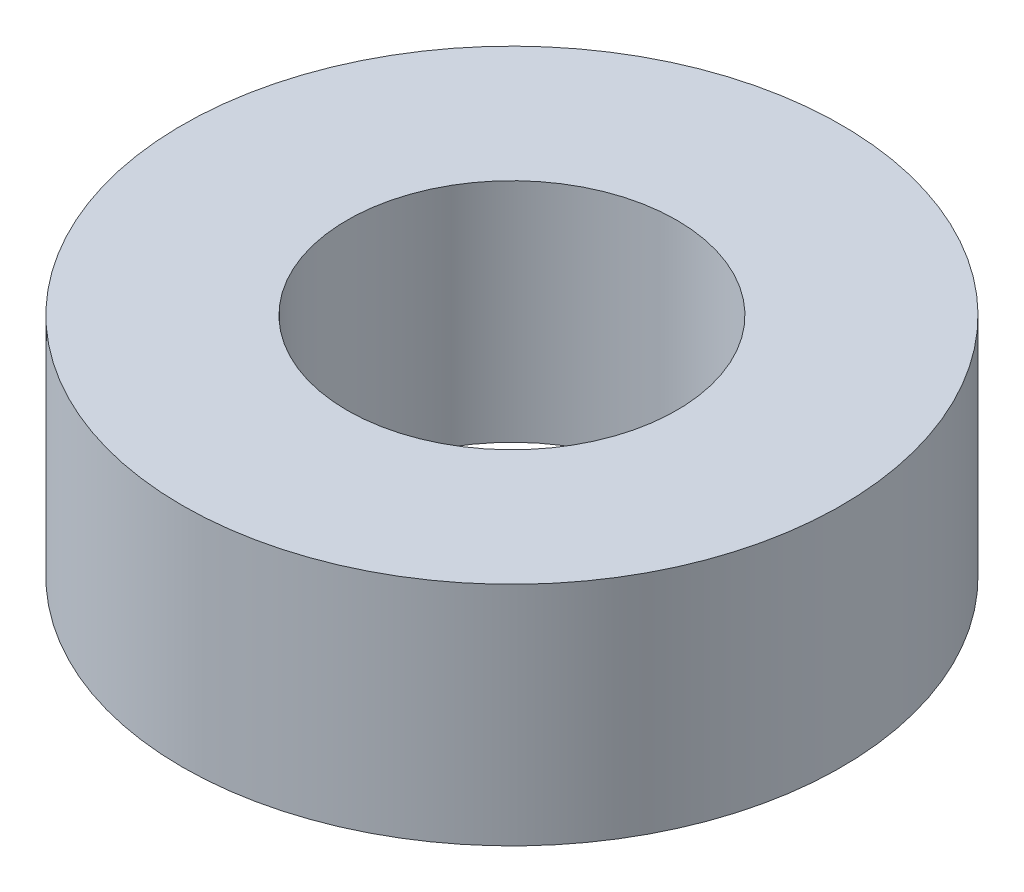
SolidWorks part; units mm, degrees
material "ABS"
ref_plane "Front Plane" through (0, 0, 0) normal (0, 0, 1) x (1, 0, 0)
ref_plane "Top Plane" through (0, 0, 0) normal (0, 1, 0) x (1, 0, 0)
ref_plane "Right Plane" through (0, 0, 0) normal (1, 0, 0) x (0, 0, -1)
sketch "Sketch1" plane through (0, 0, 0) normal (0, 1, 0) x (1, 0, 0)
  circle A0 centre (0, 0) radius 2.032
  circle A1 centre (0, 0) radius 4.064
  dimension "D1" = 4.064
  dimension "D2" = 8.128
extrude "Boss-Extrude1" add sketch "Sketch1" along normal blind 2.794
